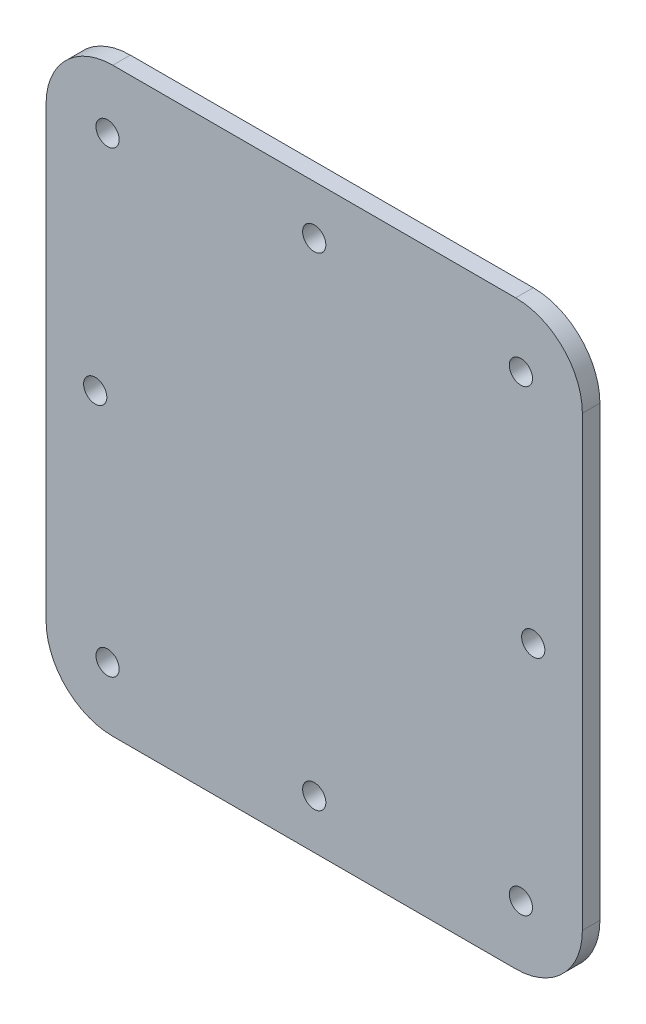
SolidWorks part; units mm, degrees
material "ABS PC"
ref_plane "X-Y Datum" through (0, 0, 0) normal (0, 0, 1) x (1, 0, 0)
ref_plane "X-Z Datum" through (0, 0, 0) normal (0, 1, 0) x (1, 0, 0)
ref_plane "Y-Z Datum" through (0, 0, 0) normal (1, 0, 0) x (0, 0, -1)
sketch "Sketch1" plane through (0, 0, 0) normal (0, 0, 1) x (1, 0, 0)
  line L7 (88.519, 156.464) -> (15.621, 156.464)
  line L22 (100.584, 63.373) -> (100.584, 144.399)
  line L23 (15.621, 51.308) -> (88.519, 51.308)
  line L24 (3.556, 144.399) -> (3.556, 63.373)
  circle A0 centre (14.6778, 145.3421) radius 2.1
  circle A1 centre (52.07, 147.574) radius 2.1
  circle A2 centre (89.4622, 145.3421) radius 2.1
  circle A3 centre (91.694, 103.886) radius 2.1
  circle A4 centre (89.4622, 62.4298) radius 2.1
  circle A5 centre (52.07, 60.198) radius 2.1
  circle A6 centre (14.6778, 62.4298) radius 2.1
  circle A7 centre (12.446, 103.886) radius 2.1
  arc A26 (88.519, 51.308) -> (100.584, 63.373) centre (88.519, 63.373) ccw
  arc A27 (3.556, 63.373) -> (15.621, 51.308) centre (15.621, 63.373) ccw
  arc A28 (15.621, 156.464) -> (3.556, 144.399) centre (15.621, 144.399) ccw
  arc A29 (100.584, 144.399) -> (88.519, 156.464) centre (88.519, 144.399) ccw
  point P24 (52.07, 103.886)
extrude "Boss-Extrude1" add sketch "Sketch1" along normal blind 3.175
